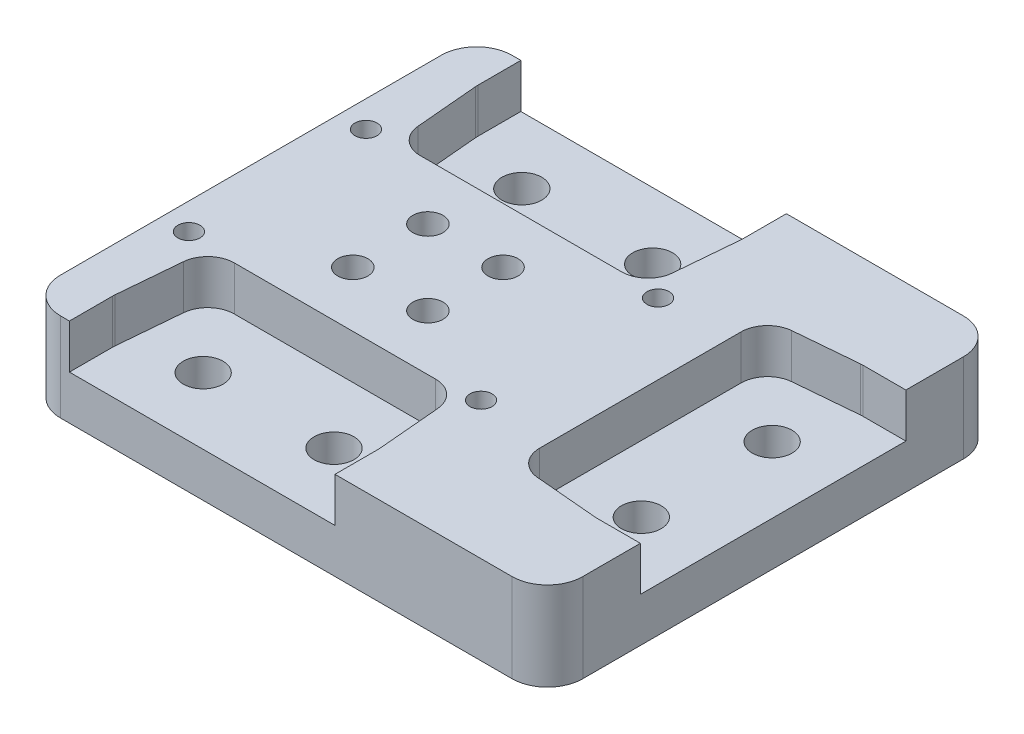
SolidWorks part; units mm, degrees
material "3.1355 (EN-AW 2024)"
ref_plane "Front" through (0, 0, 0) normal (0, 0, 1) x (1, 0, 0)
ref_plane "Top" through (0, 0, 0) normal (0, 1, 0) x (1, 0, 0)
ref_plane "Right" through (0, 0, 0) normal (1, 0, 0) x (0, 0, -1)
sketch "Эскиз1" plane through (0, 0, 0) normal (0, 1, 0) x (1, 0, 0)
  line L1 (0, 0) -> (59, 0)
  line L2 (0, 0) -> (0, 51)
  line L3 (0, 51) -> (59, 51)
  line L4 (59, 0) -> (59, 51)
  dimension "D1" = 51
  dimension "D2" = 59
extrude "Бобышка-Вытянуть1" add sketch "Эскиз1" along normal blind 10
extrude "Вырез-Вытянуть5" cut sketch "Эскиз13" against normal blind 5
sketch "Эскиз13" plane through (28.5214, 10, -17.6817) normal (0, 1, 0) x (1, 0, 0)
  line L5 (30.4786, 22.8183) -> (25.6096, 22.8183)
  line L6 (25.3482, 22.8069) -> (18.2172, 22.183)
  line L7 (15.4786, 19.1944) -> (15.4786, -3.5578)
  line L8 (18.2172, -6.5464) -> (25.3482, -7.1703)
  line L9 (25.6096, -7.1817) -> (30.4786, -7.1817)
  line L10 (30.4786, 22.8183) -> (30.4786, -7.1817)
  arc A4 (25.6096, 22.8183) -> (25.3482, 22.8069) centre (25.6096, 19.8183) ccw
  arc A5 (18.2172, 22.183) -> (15.4786, 19.1944) centre (18.4786, 19.1944) ccw
  arc A6 (15.4786, -3.5578) -> (18.2172, -6.5464) centre (18.4786, -3.5578) ccw
  arc A7 (25.3482, -7.1703) -> (25.6096, -7.1817) centre (25.6096, -4.1817) ccw
sketch "Эскиз5" plane through (0, 10, 0) normal (0, 1, 0) x (1, 0, 0)
  line L0 (20, 51) -> (20, 0) construction
  line L1 (59, 51) -> (0, 51) construction
  line L3 (15.7574, 29.7426) -> (20, 25.5) construction
  line L4 (20, 25.5) -> (14, 25.5) construction
  line L5 (24.2426, 29.7426) -> (20, 25.5) construction
  line L6 (24.2426, 21.2574) -> (20, 25.5) construction
  line L7 (15.7574, 21.2574) -> (20, 25.5) construction
  circle A0 centre (20, 25.5) radius 6 construction
  point P16 (20, 25.5)
  dimension "D1" = 12
  dimension "D2" = 45
  dimension "D3" = 4
hole_wizard "Отверстие с зазором M31" positions "Эскиз7" profile "Эскиз6" hole size "M3" standard "Ansi Metric" end condition through all
sketch "Эскиз7" plane through (0, 0, 0) normal (0, -1, 0) x (-1, 0, 0)
  point P0 (-24.2426, 29.7426)
  point P3 (-15.7574, 29.7426)
  point P6 (-15.7574, 21.2574)
  point P9 (-24.2426, 21.2574)
sketch "Эскиз6" plane through (24.2426, 0, -29.7426) normal (1, 0, 0) x (0, 0, -1)
  line L0 (0, 0) -> (0, 10)
  line L1 (0, 10) -> (1.7, 10)
  line L2 (1.7, 10) -> (1.7, 0)
  line L5 (1.7, 0) -> (0, 0)
  line L11 (0, -6.35) -> (0, 107.95) construction
  dimension "Диаметр сквозного отверстия" = 3.4
  dimension "Глубина сквозного отверстия" = 10
sketch "Эскиз8" plane through (0, 10, 0) normal (0, 1, 0) x (1, 0, 0)
  line L0 (20, 25.5) -> (150, 25.5) construction
  line L1 (59, 51) -> (0, 51) construction
  line L2 (59, 0) -> (150, 0)
  line L3 (59, 0) -> (59, 51)
  line L4 (59, 51) -> (150, 51)
  line L5 (150, 0) -> (150, 51)
  dimension "D1" = 130
extrude "Бобышка-Вытянуть2" [suppressed] add sketch "Эскиз8" against normal through all
sketch "Эскиз9" [suppressed] plane through (0, 0, 0) normal (0, -1, 0) x (1, 0, 0)
  line L0 (140, 0) -> (35, 0)
  line L1 (0, 0) -> (150, 0) construction
  line L2 (0, -51) -> (0, 0) construction
  line L3 (150, 0) -> (150, -51) construction
  line L4 (150, -25.5) -> (0, -25.5) construction
  spline S0 degree 3 poles (140, 0) (86.4416, -20.3357) (47.1176, -4.1079) (35, 0) knots 0 0 0 0 1 1 1 1
  dimension "D1" = 35
  dimension "D2" = 10
extrude "Вырез-Вытянуть3" [suppressed] cut sketch "Эскиз9" against normal blind 10
fillet "Скругление1" radius 4 2 edges at (0, 5, -51) (0, 5, 0)
fillet "Скругление2" radius 4 2 edges at (59, 5, -51) (59, 5, 0)
hole_wizard "Отверстие с зазором M41" [suppressed] positions "Эскиз11" profile "Эскиз10" hole size "M4" standard "Ansi Metric"
sketch "Эскиз11" plane through (0, 0, 0) normal (0, -1, 0) x (-1, 0, 0)
  point P0 (-51.5, 25.5)
  point P3 (-20, 43.5)
  point P6 (-20, 7.5)
sketch "Эскиз10" plane through (51.5, 0, -25.5) normal (1, 0, 0) x (0, 0, -1)
  line L0 (0, 0) -> (0, 5)
  line L1 (0, 5) -> (2.25, 5)
  line L2 (2.25, 5) -> (2.25, 0)
  line L5 (2.25, 0) -> (0, 0)
  line L11 (0, -6.35) -> (0, 107.95) construction
  dimension "Диаметр сквозного отверстия" = 4.5
  dimension "Глубина сквозного отверстия" = 5
extrude "Вырез-Вытянуть6" cut sketch "Эскиз14" against normal blind 5
sketch "Эскиз14" plane through (28.5214, 10, -17.6817) normal (0, 1, 0) x (1, 0, 0)
  line L10 (-23.5214, -12.8127) -> (-23.5214, -17.6817)
  line L11 (-22.8861, -5.4203) -> (-23.5099, -12.5512)
  line L12 (2.8548, -2.6817) -> (-19.8975, -2.6817)
  line L13 (6.4672, -12.5512) -> (5.8434, -5.4203)
  line L14 (6.4786, -17.6817) -> (6.4786, -12.8127)
  line L15 (6.4786, 28.4493) -> (6.4786, 33.3183)
  line L16 (5.8434, 21.0568) -> (6.4672, 28.1878)
  line L17 (-19.8975, 18.3183) -> (2.8548, 18.3183)
  line L18 (-23.5099, 28.1878) -> (-22.8861, 21.0568)
  line L19 (-23.5214, 33.3183) -> (-23.5214, 28.4493)
  line L21 (6.4786, 33.3183) -> (-23.5214, 33.3183)
  line L23 (-23.5214, -17.6817) -> (6.4786, -17.6817)
  arc A7 (-23.5099, -12.5512) -> (-23.5214, -12.8127) centre (-20.5214, -12.8127) ccw
  arc A8 (-19.8975, -2.6817) -> (-22.8861, -5.4203) centre (-19.8975, -5.6817) ccw
  arc A9 (5.8434, -5.4203) -> (2.8548, -2.6817) centre (2.8548, -5.6817) ccw
  arc A10 (6.4672, 28.1878) -> (6.4786, 28.4493) centre (3.4786, 28.4493) ccw
  arc A11 (2.8548, 18.3183) -> (5.8434, 21.0568) centre (2.8548, 21.3183) ccw
  arc A12 (-22.8861, 21.0568) -> (-19.8975, 18.3183) centre (-19.8975, 21.3183) ccw
  arc A13 (-23.5214, 28.4493) -> (-23.5099, 28.1878) centre (-20.5214, 28.4493) ccw
  arc A15 (6.4786, -12.8127) -> (6.4672, -12.5512) centre (3.4786, -12.8127) ccw
hole_wizard "Отверстие с зазором M42" positions "Эскиз15" profile "Эскиз16" hole size "M4" standard "Ansi Metric"
sketch "Эскиз15" plane through (28.5214, 5, -17.6817) normal (0, 1, 0) x (1, 0, 0)
  point P0 (-15.912, 25.8183)
  point P3 (-1.1307, 25.8183)
  point P6 (22.9786, 15.2089)
  point P9 (22.9786, 0.4276)
  point P12 (-1.1307, -10.1817)
  point P15 (-15.912, -10.1817)
sketch "Эскиз16" plane through (12.6094, 5, -43.5) normal (1, 0, 0) x (0, 0, 1)
  line L0 (0, 0) -> (0, 6.3509)
  line L1 (0, 6.3509) -> (2.25, 4.999)
  line L2 (2.25, 4.999) -> (2.25, 0)
  line L3 (2.25, 0) -> (0, 0)
  line L4 (0, 6.3509) -> (-2.25, 4.999) construction
  line L5 (0, -6.35) -> (0, 107.95) construction
  dimension "Диаметр отверстия" = 4.5
  dimension "Глубина отверстия" = 4.999
  dimension "Угол заточки сверла" = 118
hole_wizard "Отверстие обработанное метчиком M3x0.51" positions "Эскиз18" profile "Эскиз19" tap size "M3x0.5" standard "Ansi Metric" end condition through all
sketch "Эскиз18" plane through (33.5004, 0, -26.4103) normal (0, -1, 0) x (-1, 0, 0)
  point P0 (30.5004, -10.9103)
  point P3 (-2.4996, -10.9103)
  point P6 (-2.4996, 9.0897)
  point P9 (30.5004, 9.0897)
sketch "Эскиз19" plane through (3, 0, -15.5) normal (1, 0, 0) x (0, 0, -1)
  line L0 (0, 0) -> (0, 10)
  line L1 (0, 10) -> (1.25, 10)
  line L2 (1.25, 10) -> (1.25, 0)
  line L3 (1.25, 0) -> (0, 0)
  line L4 (0, -6.35) -> (0, 107.95) construction
  dimension "Диаметр проходного сверла" = 2.5
  dimension "Глубина проходного сверла" = 10
cosmetic thread "Отверстие резьбы1" parameters "D2"=3
cosmetic thread "Отверстие резьбы2" parameters "D2"=3
cosmetic thread "Отверстие резьбы3" parameters "D2"=3
cosmetic thread "Отверстие резьбы4" parameters "D2"=3
